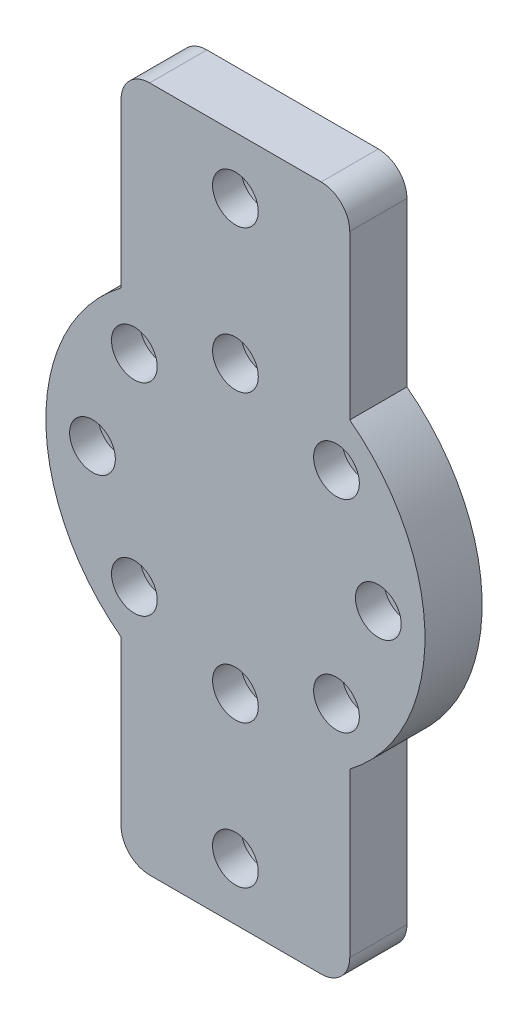
SolidWorks part; units mm, degrees
ref_plane "Alzado" through (0, 0, 0) normal (0, 0, 1) x (1, 0, 0)
ref_plane "Planta" through (0, 0, 0) normal (0, 1, 0) x (1, 0, 0)
ref_plane "Vista lateral" through (0, 0, 0) normal (1, 0, 0) x (0, 0, -1)
sketch "Model" plane through (0, 0, 0) normal (0, 0, 1) x (1, 0, 0)
  line L0 (-25, 0) -> (25, 0) construction
  line L1 (0, 0) -> (0, 43.0073) construction
  line L2 (0, 0) -> (0, -58.9979) construction
  line L3 (-15, 60) -> (15, 60)
  line L4 (-15.0112, -60) -> (15, -60)
  line L9 (20, 55) -> (20, 26.4426)
  line L10 (-20, 55) -> (-20, 26.4426)
  line L11 (-20, -26.4426) -> (20, -26.4426) construction
  line L12 (-20, 26.4426) -> (20, 26.4426) construction
  line L14 (-20, -26.4426) -> (-20, -54.6655)
  line L15 (20, -26.4426) -> (20, -55)
  arc A0 (-20, 26.4426) -> (-20, -26.4426) centre (0, 0) ccw
  circle A1 centre (-17.6777, 17.6777) radius 2.6
  circle A2 centre (0, 25) radius 2.6
  circle A3 centre (-25, 0) radius 2.6
  circle A4 centre (17.6777, 17.6777) radius 2.6
  circle A5 centre (25, 0) radius 2.6
  circle A6 centre (17.6777, -17.6777) radius 2.6
  circle A7 centre (0, -25) radius 2.6
  circle A8 centre (-17.6777, -17.6777) radius 2.6
  circle A9 centre (0, 50) radius 4
  circle A10 centre (0, -50) radius 4
  arc A13 (-15.0112, -60) -> (-20, -54.6655) centre (-15.0112, -55) cw
  arc A15 (15, 60) -> (20, 55) centre (15, 55) cw
  arc A16 (-15, 60) -> (-20, 55) centre (-15, 55) ccw
  arc A17 (20, -26.4426) -> (20, 26.4426) centre (0, 0) ccw
  arc A18 (15, -60) -> (20, -55) centre (15, -55) ccw
  point P22 (0, 0)
  dimension "D1" = 5
  dimension "D6" = 8
  dimension "D7" = 8
  dimension "D11" = 20
  dimension "D17" = 5
  dimension "D18" = 5
  dimension "D16" = 5
  dimension "D2" = 25
  dimension "D4" = 60
  dimension "D5" = 60
  dimension "D8" = 10
  dimension "D9" = 0
  dimension "D10" = 10
  dimension "D12" = 20
  dimension "D13" = 20
  dimension "D14" = 20
  dimension "D15" = 28.2229
  dimension "D3" = 8
extrude "Saliente-Extruir1" add sketch "Model" along normal blind 10
sketch "Croquis3" plane through (0, 0, 10) normal (0, 0, 1) x (1, 0, 0)
  circle A0 centre (25, 0) radius 4
  circle A1 centre (17.6777, -17.6777) radius 4
  circle A2 centre (0, -25) radius 4
  circle A3 centre (-17.6777, -17.6777) radius 4
  circle A4 centre (-25, 0) radius 4
  circle A5 centre (-17.6777, 17.6777) radius 4
  circle A6 centre (0, 25) radius 4
  circle A7 centre (17.6777, 17.6777) radius 4
  point P20 (0, 0)
  dimension "D1" = 8
extrude "Cortar-Extruir1" cut sketch "Croquis3" against normal blind 5
sketch "Croquis4" plane through (0, 0, 0) normal (0, 0, -1) x (-1, 0, 0)
  line L0 (0, 0) -> (18.8188, 0) construction
  circle A0 centre (0, 50) radius 7
  circle A1 centre (0, -50) radius 7
  dimension "D1" = 14
extrude "Cortar-Extruir2" cut sketch "Croquis4" against normal blind 5
